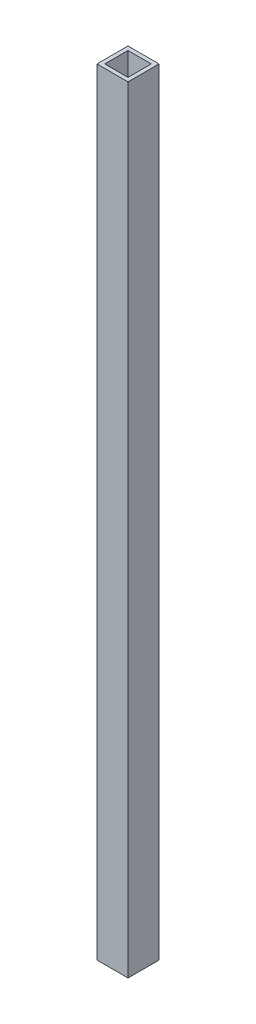
SolidWorks part; units mm, degrees
ref_plane "Front Plane" through (0, 0, 0) normal (0, 0, 1) x (1, 0, 0)
ref_plane "Top Plane" through (0, 0, 0) normal (0, 1, 0) x (1, 0, 0)
ref_plane "Right Plane" through (0, 0, 0) normal (1, 0, 0) x (0, 0, -1)
sketch "Sketch1" plane through (0, 0, 0) normal (0, 1, 0) x (1, 0, 0)
  line L1 (0, 0) -> (2.54, 0)
  line L2 (0, 0) -> (0, 2.54)
  line L3 (0, 2.54) -> (2.54, 2.54)
  line L4 (2.54, 0) -> (2.54, 2.54)
  dimension "D1" = 2.54
  dimension "D2" = 2.54
extrude "Boss-Extrude1" add sketch "Sketch1" along normal blind 63.5
sketch "Sketch2" plane through (0, 63.5, 0) normal (0, 1, 0) x (1, 0, 0)
  line L0 (2.54, 2.54) -> (0, 2.54) construction
  line L1 (0.3175, 0.3175) -> (2.2225, 0.3175)
  line L2 (0.3175, 0.3175) -> (0.3175, 2.2225)
  line L3 (0.3175, 2.2225) -> (2.2225, 2.2225)
  line L4 (2.2225, 0.3175) -> (2.2225, 2.2225)
  line L5 (0, 2.54) -> (0, 0) construction
  dimension "D1" = 1.905
  dimension "D2" = 0.3175
  dimension "D3" = 0.3175
extrude "Cut-Extrude1" cut sketch "Sketch2" against normal through all
